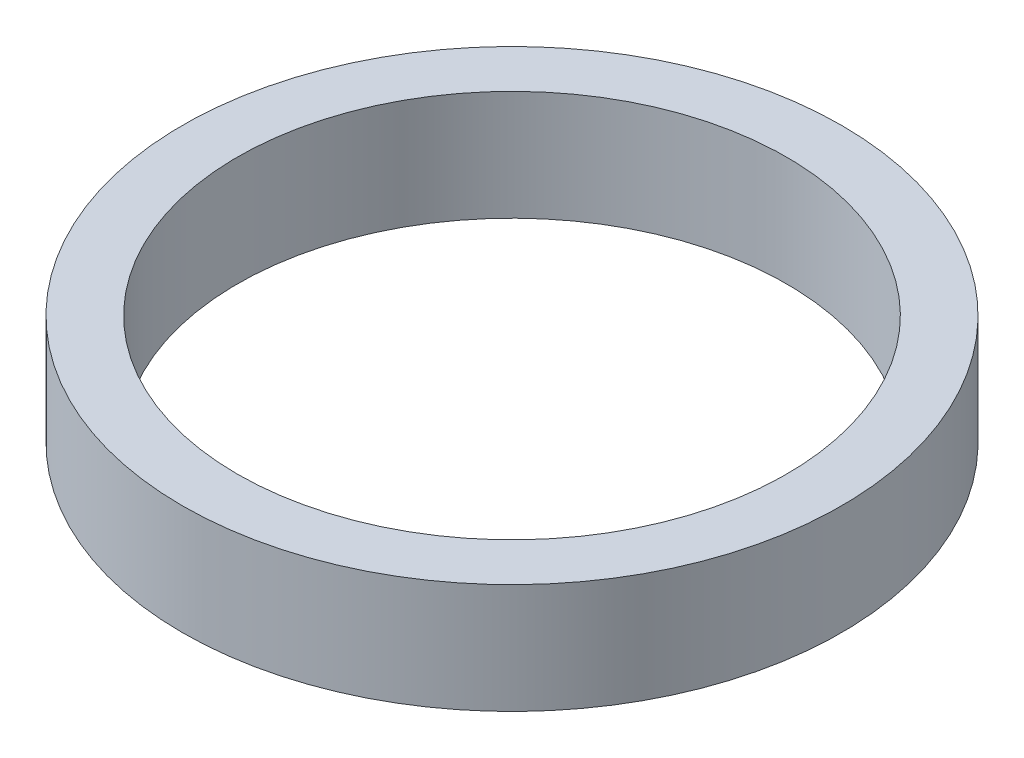
SolidWorks part; units mm, degrees
ref_plane "Front Plane" through (0, 0, 0) normal (0, 0, 1) x (1, 0, 0)
ref_plane "Top Plane" through (0, 0, 0) normal (0, 1, 0) x (1, 0, 0)
ref_plane "Right Plane" through (0, 0, 0) normal (1, 0, 0) x (0, 0, -1)
sketch "Sketch1" plane through (0, 0, 0) normal (0, 1, 0) x (1, 0, 0)
  circle A0 centre (0, 0) radius 12.5
  circle A1 centre (0, 0) radius 15
  dimension "D1" = 30
  dimension "D2" = 25
extrude "Boss-Extrude1" add sketch "Sketch1" along normal blind 5
equation "\"column angle\" = 45deg "
equation "\"short_bearing_outer_width\" = 10mm "
equation "\"wheel base\" = 1561mm "
equation "\"track\" = 1354mm "
equation "\"turning radius\" = 2000mm "
equation "\"turn to lock\" = 0.75mm "
equation "\"steering arm length\" = 100mm "
equation "\"primary shaft small diameter\" = 16mm "
equation "\"primary shaft large diameter\" = 24mm "
equation "\"secondary shaft small diameter\" = 16mm "
equation "\"secondary shaft large diameter\" = 25mm "
equation "\"steering column length\" = 555mm "
equation "\"keyway_height\" = 1.39mm "
equation "\"keyway_width\" = 2.78mm "
equation "\"keyway_length\" = 30mm "
equation "\"steering wheel bolt width\" = 6mm "
equation "\"steering wheel bolt length\" = 40mm "
equation "\"bushing length\" = 40mm "
equation "\"bushing thickness\" = 3mm "
equation "\"u_joint clearance\" = 30mm "
equation "\"u_joint thickness\" = 7.5mm "
equation "\"horizontal shaft length\" = 90mm "
equation "\"column bushing diameter\" = \"primary shaft small diameter\" + 4 "
equation "\"column bushing distance\" = \"steering column length\"/4 "
equation "\"pinion width\" = 26.5mm "
equation "\"pin hole diameter\" = 10mm "
equation "\"rack hole to hole\" = 500mm "
equation "\"rack length\" = \"rack hole to hole\" + \"pin hole diameter\"*2 "
equation "\"max turning angle\" = atn(\"wheel base\" / (\"turning radius\" - 0.5 * \"track\")) "
equation "\"max travel\" = 2 * \"steering arm length\" * sin(0.5 * \"max turning angle\") "
equation "\"pitch diameter\" = \"max travel\"/(pi * \"turn to lock\") "
equation "\"number of teeth\" = 18mm "
equation "\"pressure angle\" = 20deg "
equation "\"module\" = \"pitch diameter\" / \"number of teeth\" "
equation "\"tie rod length\" = 305mm "
equation "\"tie rod inner diameter\" = 6.6mm "
equation "\"tie rod outer diameter\" = 8.1mm "
equation "\"D1@Sketch1\"=\"secondary shaft large diameter\"+5"
equation "\"D2@Sketch1\"=\"secondary shaft large diameter\""
